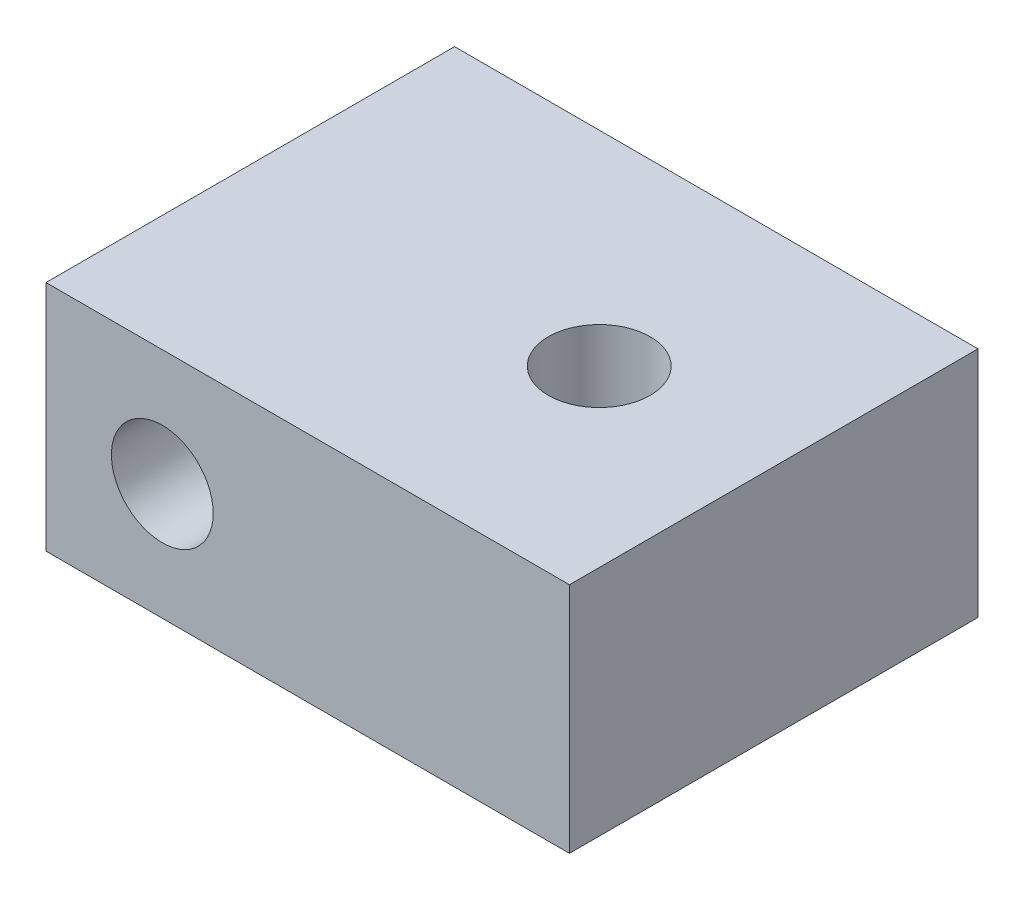
SolidWorks part; units mm, degrees
ref_plane "Front Plane" through (0, 0, 0) normal (0, 0, 1) x (1, 0, 0)
ref_plane "Top Plane" through (0, 0, 0) normal (0, 1, 0) x (1, 0, 0)
ref_plane "Right Plane" through (0, 0, 0) normal (1, 0, 0) x (0, 0, -1)
sketch "Sketch1" plane through (0, 0, 0) normal (0, 0, 1) x (1, 0, 0)
  line L1 (-3.6971, 3.7062) -> (4.3029, 3.7062)
  line L2 (-3.6971, 3.7062) -> (-3.6971, -4.2938)
  line L3 (-3.6971, -4.2938) -> (4.3029, -4.2938)
  line L4 (4.3029, 3.7062) -> (4.3029, -4.2938)
  dimension "D1" = 8
extrude "Boss-Extrude1" add sketch "Sketch1" along normal blind 14.05
sketch "Sketch2" plane through (0, 0, 14.05) normal (0, 0, 1) x (1, 0, 0)
  line L2 (0.3029, -4.2938) -> (0.3029, 3.7062) construction
  line L3 (-3.6971, -4.2938) -> (4.3029, -4.2938) construction
  line L4 (4.3029, 3.7062) -> (-3.6971, 3.7062) construction
  line L5 (-3.6971, -0.2938) -> (4.3029, -0.2938) construction
  line L6 (-3.6971, 3.7062) -> (-3.6971, -4.2938) construction
  line L7 (4.3029, -4.2938) -> (4.3029, 3.7062) construction
  circle A0 centre (0.3029, -0.2938) radius 1.75
  dimension "D1" = 3.5
extrude "Cut-Extrude1" cut sketch "Sketch2" against normal through all
sketch "Sketch3" plane through (4.3029, 0, 0) normal (1, 0, 0) x (0, 0, -1)
  line L4 (0, -4.2938) -> (0, 3.7062)
  line L5 (0, 3.7062) -> (-14.05, 3.7062)
  line L6 (-14.05, 3.7062) -> (-14.05, -4.2938)
  line L7 (-14.05, -4.2938) -> (0, -4.2938)
  line L8 (0, -4.2938) -> (0, 3.7062)
  line L9 (0, 3.7062) -> (-14.05, 3.7062)
  line L10 (-14.05, 3.7062) -> (-14.05, -4.2938)
  line L11 (-14.05, -4.2938) -> (0, -4.2938)
  dimension "D1" = 0
extrude "Boss-Extrude2" add sketch "Sketch3" along normal blind 10
sketch "Sketch4" plane through (0, 3.7062, 0) normal (0, 1, 0) x (1, 0, 0)
  line L0 (14.3029, -7.025) -> (4.6937, -7.025) construction
  line L1 (14.3029, 0) -> (14.3029, -14.05) construction
  circle A0 centre (8.3029, -7.025) radius 1.75
  dimension "D1" = 3.5
  dimension "D2" = 6
extrude "Cut-Extrude2" cut sketch "Sketch4" against normal through all
